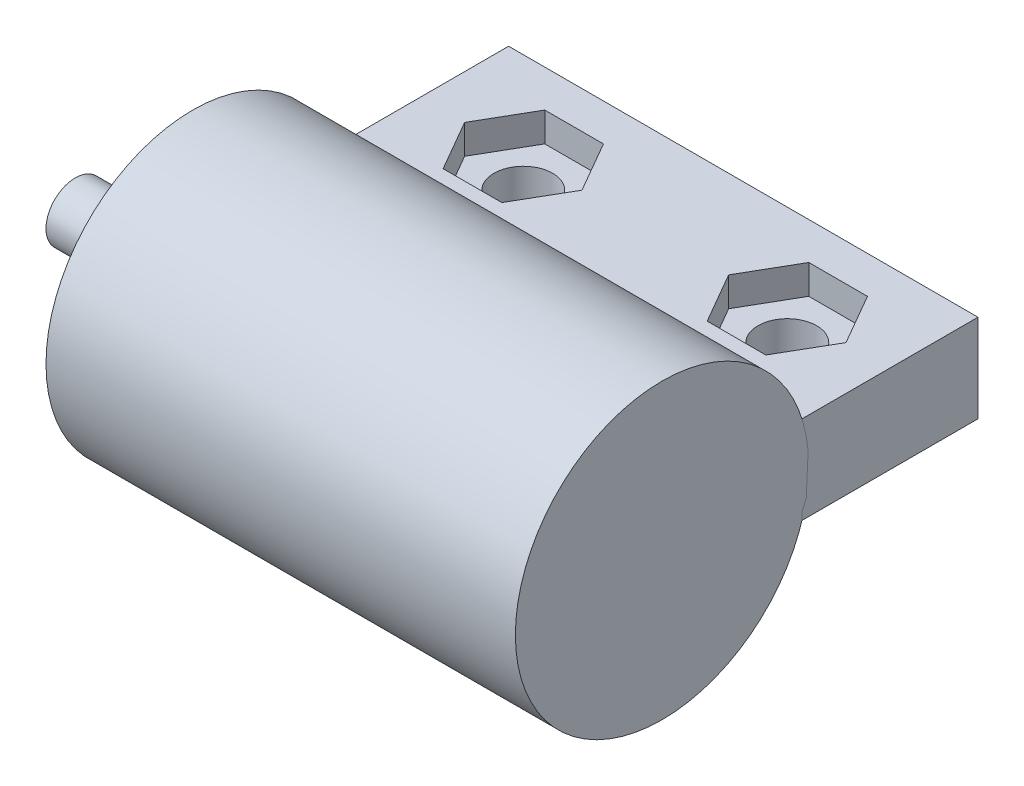
SolidWorks part; units mm, degrees
ref_plane "前视基准面" through (0, 0, 0) normal (0, 0, 1) x (1, 0, 0)
ref_plane "上视基准面" through (0, 0, 0) normal (0, 1, 0) x (1, 0, 0)
ref_plane "右视基准面" through (0, 0, 0) normal (1, 0, 0) x (0, 0, -1)
other "Configuration Table"
sketch "草图1" plane through (0, 0, 0) normal (0, 1, 0) x (1, 0, 0)
  line L0 (0, 1.5) -> (8, 1.5) construction
  line L1 (0, 0) -> (8, 0)
  line L2 (0, 0) -> (0, 3)
  line L3 (0, 3) -> (8, 3)
  line L4 (8, 0) -> (8, 3)
  circle A0 centre (1.75, 1.5) radius 0.5
  circle A1 centre (6.25, 1.5) radius 0.5
  dimension "D3" = 1
  dimension "D4" = 1
  dimension "D1" = 8
  dimension "D2" = 3
  dimension "D5" = 1.75
  dimension "D6" = 1.75
extrude "凸台-拉伸1" add sketch "草图1" along normal blind 1
sketch "草图2" plane through (0, 1, 0) normal (0, 1, 0) x (1, 0, 0)
  line L0 (4, 3) -> (4, 0) construction
  line L1 (8, 3) -> (0, 3) construction
  line L2 (0, 0) -> (8, 0) construction
  line L3 (0, 1.5) -> (4, 1.5) construction
  line L4 (0, 3) -> (0, 0) construction
  line L5 (0, 3) -> (4, 3)
  line L6 (1.75, 3) -> (1.75, 0) construction
  line L7 (2.25, 2.366) -> (1.25, 2.366)
  line L8 (2.25, 2.366) -> (2.75, 1.5)
  line L9 (1.25, 2.366) -> (0.75, 1.5)
  line L10 (2.25, 0.634) -> (2.75, 1.5)
  line L11 (2.25, 0.634) -> (1.25, 0.634)
  line L12 (1.25, 0.634) -> (0.75, 1.5)
  line L13 (5.75, 2.366) -> (5.25, 1.5)
  line L14 (5.75, 0.634) -> (5.25, 1.5)
  line L15 (5.75, 0.634) -> (6.75, 0.634)
  line L16 (6.75, 0.634) -> (7.25, 1.5)
  line L17 (6.75, 2.366) -> (7.25, 1.5)
  line L18 (5.75, 2.366) -> (6.75, 2.366)
  line L19 (1.75, 2) -> (1.75, 1) construction
  circle A0 centre (1.75, 1.5) radius 0.5 construction
  point P19 (1.75, 2.366)
  line M10 (0, 3) -> (0, 0)
  line M11 (0, 0) -> (8, 0)
  line M12 (8, 0) -> (8, 3)
  line M13 (8, 3) -> (0, 3)
  dimension "D1" = 60
  dimension "D2" = 0.5
  dimension "D3" = 1
extrude "凸台-拉伸2" add sketch "草图2" along normal blind 0.5 contours L11 L12 L9 L7 L8 L10 L13 L18 L17 L16 L15 L14 M13 M10 M11 M12
sketch "草图3" plane through (8, 0, 0) normal (1, 0, 0) x (0, 0, -1)
  line L0 (5, 0.75) -> (0, 0.75) construction
  line L6 (3, 1.5) -> (3, 0)
  circle A0 centre (-2.3848, 0.75) radius 2.5
  point P8 (3, 0.75)
  dimension "D1" = 5
extrude "凸台-拉伸3" add sketch "草图3" against normal up to surface (8 mm away) separate body contours A0 up to face at (0, 0.75, -1.5)
sketch "草图5" plane through (0, 0, 0) normal (-1, 0, 0) x (0, 0, 1)
  circle A0 centre (2.3848, 0.75) radius 0.5
  dimension "D1" = 1
extrude "凸台-拉伸4" add sketch "草图5" along normal blind 2
